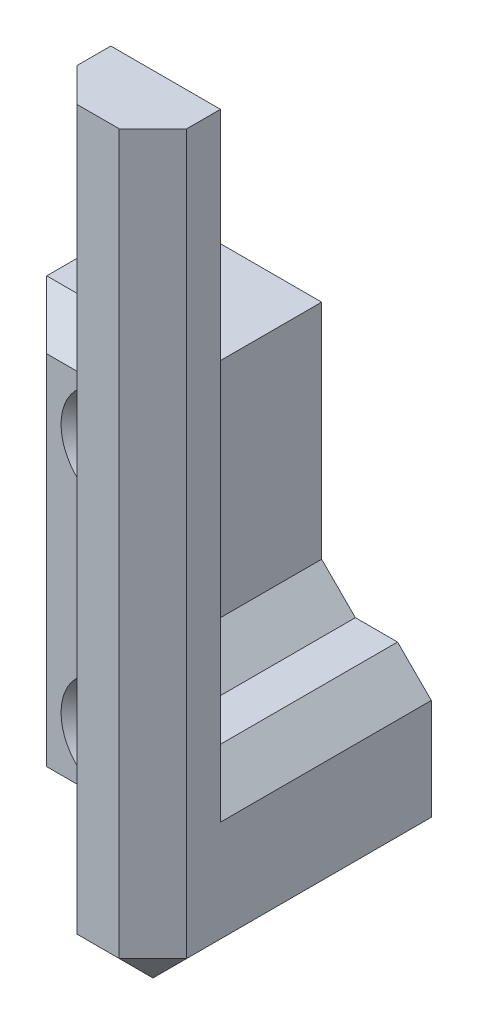
SolidWorks part; units mm, degrees
ref_plane "Front Plane" through (0, 0, 0) normal (0, 0, 1) x (1, 0, 0)
ref_plane "Top Plane" through (0, 0, 0) normal (0, 1, 0) x (1, 0, 0)
ref_plane "Right Plane" through (0, 0, 0) normal (1, 0, 0) x (0, 0, -1)
sketch "Sketch1" plane through (0, 0, 0) normal (0, 0, 1) x (1, 0, 0)
  line L0 (0, 12.6) -> (8, 12.6) construction
  line L1 (0, 0) -> (8, 0)
  line L2 (0, 0) -> (0, 25.2)
  line L3 (0, 25.2) -> (8, 25.2)
  line L5 (4, 25.2) -> (4, 0) construction
  line L6 (6, 25.2) -> (6, 0) construction
  line L8 (8, 0) -> (9.5, 0)
  line L10 (8, 25.2) -> (9.5, 25.2)
  line L11 (9.5, 0) -> (9.5, 25.2)
  circle A0 centre (6, 20) radius 1.6
  circle A1 centre (6, 5.2) radius 1.6
  dimension "D4" = 3.2
  dimension "D1" = 25.2
  dimension "D2" = 8
  dimension "D5" = 7.4
  dimension "D6" = 1.5
extrude "Boss-Extrude1" add sketch "Sketch1" along normal blind 8.8
sketch "Sketch2" plane through (0, 0, 8.8) normal (0, 0, 1) x (1, 0, 0)
  line L0 (9.5, 0) -> (9.5, 25.2) construction
  line L1 (9.5, 0) -> (16, 0)
  line L2 (9.5, 0) -> (9.5, 10)
  line L3 (9.5, 10) -> (16, 10)
  line L4 (16, 0) -> (16, 10)
  dimension "D1" = 6.5
  dimension "D2" = 10
extrude "Boss-Extrude2" add sketch "Sketch2" along normal blind 3.7 and the other way up to surface other way up to face at (7.6, 20, 0)
sketch "Sketch3" plane through (0, 0, 12.5) normal (0, 0, 1) x (1, 0, 0)
  line L0 (16, 0) -> (16, 10) construction
  line L1 (9.5, 0) -> (16, 0)
  line L2 (9.5, 0) -> (9.5, 44.6)
  line L3 (9.5, 44.6) -> (16, 44.6)
  line L4 (16, 0) -> (16, 44.6)
  line L5 (9.5, 25.2) -> (0, 25.2) construction
  point P9 (4.75, 25.2)
  dimension "D1" = 19.4
extrude "Boss-Extrude3" add sketch "Sketch3" along normal blind 4
chamfer "Chamfer1" distance 2 angle 45 10 edges at (16, 10, 6.25) (4.75, 25.2, 8.8) (16, 0, 8.25) (16, 22.3, 16.5) (12.75, 0, 16.5) (9.5, 22.3, 16.5) (9.5, 0, 12.65) (4.75, 0, 8.8) (0, 12.6, 8.8) (9.5, 10, 4.4)
chamfer "Chamfer2" distance 1.55 angle 45 2 edges at (4.4, 5.2, 8.8) (7.6, 20, 8.8)
